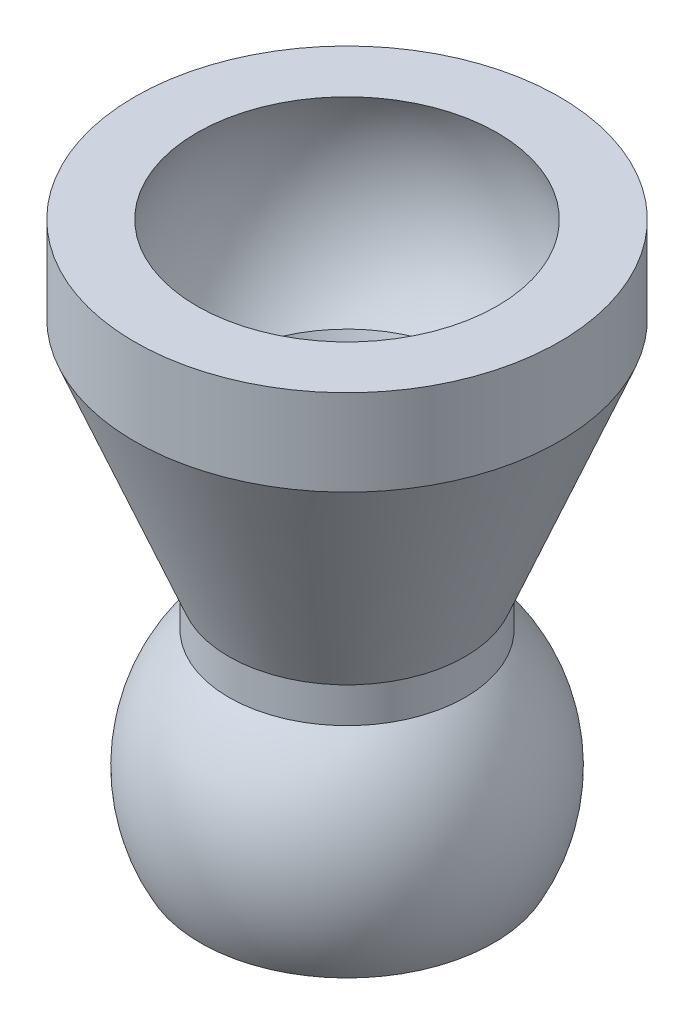
SolidWorks part; units mm, degrees
ref_plane "Alzado" through (0, 0, 0) normal (0, 0, 1) x (1, 0, 0)
ref_plane "Planta" through (0, 0, 0) normal (0, 1, 0) x (1, 0, 0)
ref_plane "Vista lateral" through (0, 0, 0) normal (1, 0, 0) x (0, 0, -1)
sketch "Croquis1" plane through (0, 0, 0) normal (0, 0, 1) x (1, 0, 0)
  line L0 (0, 0) -> (15.6274, 0)
  line L1 (0, 0) -> (0, -3.17)
  line L2 (7.8137, 0) -> (7.8137, -11.76)
  line L3 (7.8137, -11.76) -> (3.465, -11.76)
  line L4 (0, -3.17) -> (3.465, -11.76)
  line L5 (3.465, -11.76) -> (3.465, -13.06)
  line L6 (12.1624, -11.76) -> (12.1624, -13.06)
  line L7 (15.6274, 0) -> (15.6274, -3.17)
  line L8 (15.6274, -3.17) -> (12.1624, -11.76)
  line L9 (3.465, -13.06) -> (7.8137, -17.4087)
  line L10 (12.1624, -13.06) -> (7.8137, -17.4087)
  line L11 (3.465, -13.06) -> (3.465, -20.36)
  line L12 (0.96, -20.36) -> (7.8137, -20.36)
  line L13 (7.8137, -20.36) -> (7.8137, -11.76)
  line L14 (5.165, -11.43) -> (3.2627, -6.7141)
  line L15 (3.9096, -19.5442) -> (4.3558, -20.36)
  line L16 (5.165, -11.43) -> (5.165, -13.8328)
  line L17 (7.8137, -2.6261) -> (9.4524, -2.6261)
  line L19 (1.7, 0) -> (1.7, -2.84) construction
  line L20 (1.7, -2.84) -> (5.165, -11.43) construction
  arc A0 (3.465, -13.06) -> (2.4181, -20.36) centre (7.8137, -17.4087) ccw
  arc A1 (1.7, -2.84) -> (2.2886, 0) centre (7.8137, -2.6261) cw
  arc A2 (5.165, -13.8328) -> (3.9096, -19.5442) centre (7.8137, -17.4087) ccw
  arc A3 (1.7, -2.84) -> (3.2627, -6.7141) centre (7.8137, -2.6261) ccw
  dimension "D1" = 1.7
revolve "Revolución1" add sketch "Croquis1" angle 360 about L2
